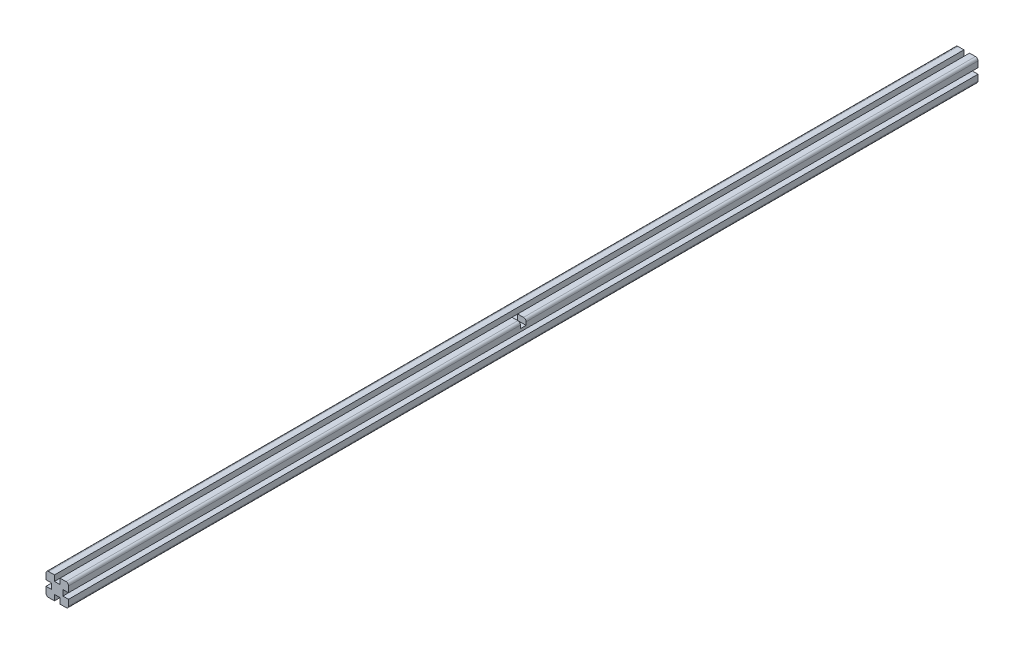
SolidWorks part; units mm, degrees
ref_plane "Front Plane" through (0, 0, 0) normal (0, 0, 1) x (1, 0, 0)
ref_plane "Top Plane" through (0, 0, 0) normal (0, 1, 0) x (1, 0, 0)
ref_plane "Right Plane" through (0, 0, 0) normal (1, 0, 0) x (0, 0, -1)
sketch "Sketch1" plane through (0, 0, 0) normal (0, 0, 1) x (1, 0, 0)
  line L0 (0, 0) -> (0, -50000) construction
  line L1 (-15.5, -20) -> (-5, -20)
  line L2 (-20, -15.5) -> (-20, -5)
  line L3 (-15.5, 20) -> (-15, 20)
  line L4 (20, -15.5) -> (20, -5)
  line L5 (-20, -20) -> (20, 20) construction
  line L6 (-20, 20) -> (20, -20) construction
  line L8 (-5, -20) -> (-5, -10)
  line L9 (-5, -10) -> (5, -10)
  line L10 (5, -20) -> (5, -10)
  line L15 (5, -20) -> (15.5, -20)
  line L16 (-8, 20) -> (-5, 20)
  line L18 (-15, 20) -> (-8, 20)
  line L19 (-20, 5) -> (-10, 5)
  line L20 (-10, 5) -> (-10, -5)
  line L21 (-20, -5) -> (-10, -5)
  line L22 (5, 20) -> (5, 10)
  line L23 (5, 10) -> (-5, 10)
  line L24 (-5, 20) -> (-5, 10)
  line L25 (20, -5) -> (10, -5)
  line L26 (10, -5) -> (10, 5)
  line L27 (20, 5) -> (10, 5)
  line L28 (-20, 5) -> (-20, 15.5)
  line L29 (5, 20) -> (15.5, 20)
  line L30 (20, 5) -> (20, 15.5)
  arc A0 (-20, 15.5) -> (-15.5, 20) centre (-15.5, 15.5) cw
  arc A1 (-15.5, -20) -> (-20, -15.5) centre (-15.5, -15.5) cw
  arc A2 (15.5, -20) -> (20, -15.5) centre (15.5, -15.5) ccw
  arc A3 (15.5, 20) -> (20, 15.5) centre (15.5, 15.5) cw
  point P0 (0, 0)
  point P41 (0, 0)
  dimension "D8" = 4.5
  dimension "D1" = 40
  dimension "D2" = 40
  dimension "D3" = 15
  dimension "D4" = 10
  dimension "D5" = 5
  dimension "D6" = 28
  dimension "D7" = 4
extrude "Boss-Extrude1" add sketch "Sketch1" along normal blind 1615
sketch "Skizze1" plane through (20, 0, 0) normal (1, 0, 0) x (0, 0, -1)
  line L0 (-807.5, 15.5) -> (-807.5, -49984.5) construction
  line L1 (-1615, 15.5) -> (0, 15.5) construction
  line L2 (-1615, 10) -> (0, 10) construction
  line L3 (-1615, 10) -> (0, 10) construction
  line L4 (-1615, 20) -> (0, 20) construction
  line L5 (-812.5, 10) -> (-802.5, 10)
  line L6 (-812.5, 10) -> (-812.5, 20)
  line L7 (-812.5, 20) -> (-802.5, 20)
  line L8 (-802.5, 10) -> (-802.5, 20)
  point P4 (-807.5, 15.5)
  dimension "D1" = 10
extrude "Schnitt-Linear austragen1" cut sketch "Skizze1" against normal up to next
